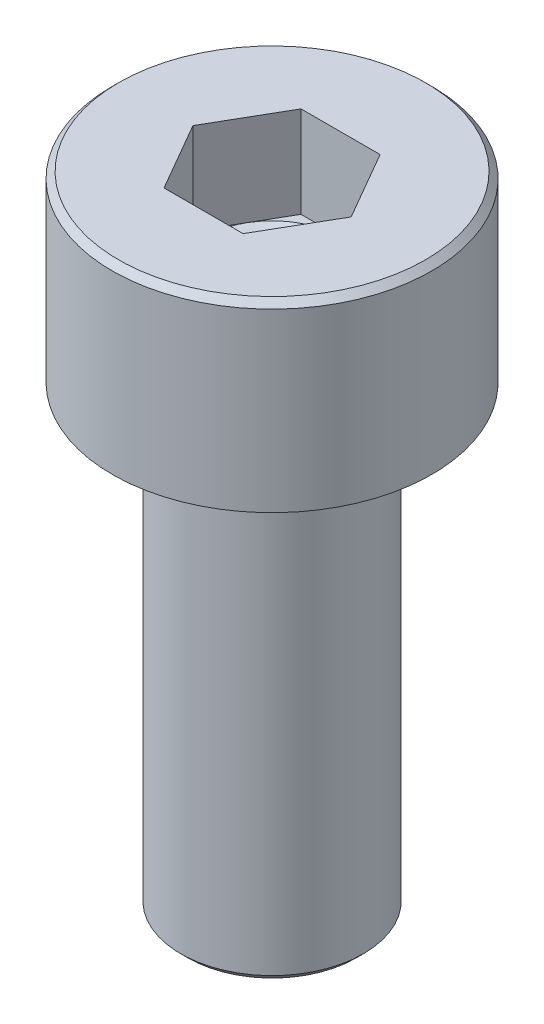
SolidWorks part; units mm, degrees
ref_plane "前视基准面" through (0, 0, 0) normal (0, 0, 1) x (1, 0, 0)
ref_plane "上视基准面" through (0, 0, 0) normal (0, 1, 0) x (1, 0, 0)
ref_plane "右视基准面" through (0, 0, 0) normal (1, 0, 0) x (0, 0, -1)
sketch "草图1" plane through (0, 0, 0) normal (0, 0, 1) x (1, 0, 0)
  line L0 (0, 0) -> (0, -14) construction
  line L1 (-2, -4) -> (-3.5, -4)
  line L2 (-2, -4) -> (-2, -14)
  line L3 (-2, -14) -> (0, -14)
  line L6 (-1.5, 0) -> (-1.5, -2)
  line L7 (-1.5, -2) -> (0, -2.866)
  line L11 (-2, -4) -> (-3.5, -4)
  line L12 (-3.5, -4) -> (-3.5, 0)
  line L13 (-3.5, 0) -> (0, 0)
  point P0 (-0.75, -14)
  dimension "D1" = 60
  dimension "M" = 4
  dimension "L" = 10
  dimension "t" = 2
  dimension "B" = 3
  dimension "E" = 4
  dimension "A" = 7
  dimension "(d)" = 1.5
sketch "草图2" plane through (0, 0, 0) normal (0, 0, 1) x (1, 0, 0)
  line L0 (-1.5, 0) -> (-1.5, -2) construction
  line L1 (-1.5, -2) -> (0, -2.866) construction
  line L3 (-2, -4) -> (-2, -14) construction
  line L4 (-2, -4) -> (-3.5, -4) construction
  line L7 (-1.5, 0) -> (-1.5, -2)
  line L8 (-1.5, -2) -> (0, -2.866)
  line L9 (-3.5, -4) -> (-3.5, 0) construction
  line L10 (-2, -4) -> (-2, -14)
  line L14 (0, -2.866) -> (0, -14)
  line L16 (-2, -14) -> (0, -14) construction
  line L19 (-2, -14) -> (0, -14)
  line L20 (-3.5, 0) -> (0, 0) construction
  line L21 (-2, -4) -> (-3.5, -4)
  line L22 (-3.5, -4) -> (-3.5, 0)
  line L23 (-3.5, 0) -> (-1.5, 0)
revolve "旋转1" add sketch "草图2" angle 360 mid plane about L14
cosmetic thread "装饰螺纹线1" parameters "D1"=10, "D2"=3.52
chamfer "倒角1" distance 0.16 angle 45 1 edges at (-2, -14, 0)
chamfer "倒角2" distance 0.14 angle 45 1 edges at (-3.5, 0, 0)
sketch "草图3" plane through (0, 0, 0) normal (0, 1, 0) x (-1, 0, 0)
  line L1 (-0.866, 1.5) -> (-1.7321, 0)
  line L2 (-1.7321, 0) -> (-0.866, -1.5)
  line L3 (-0.866, -1.5) -> (0.866, -1.5)
  line L4 (0.866, -1.5) -> (1.7321, 0)
  line L5 (1.7321, 0) -> (0.866, 1.5)
  line L6 (0.866, 1.5) -> (-0.866, 1.5)
  circle A0 centre (0, 0) radius 1.5 construction
extrude "切除-拉伸1" cut sketch "草图3" against normal up to vertex (2 mm away) up to point (-1.5, -2, 0)
sketch "草图4" plane through (0, -14, 0) normal (0, -1, 0) x (1, 0, 0)
  circle A0 centre (0, 0) radius 0.75
extrude "切除-拉伸2" cut sketch "草图4" against normal up to vertex up to point (0, 0, 0)
